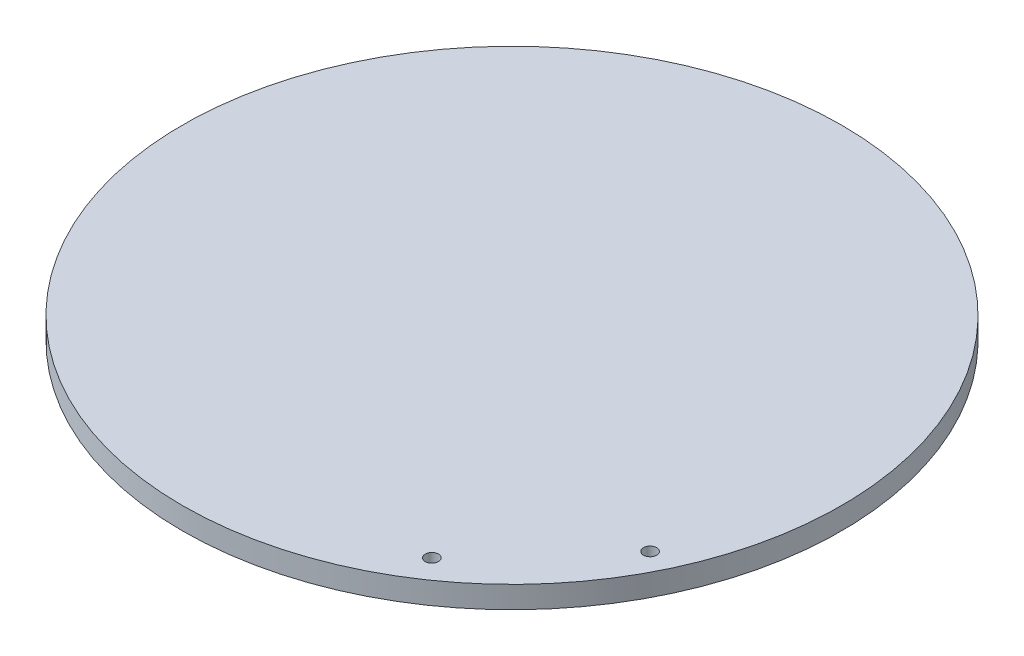
SolidWorks part; units mm, degrees
ref_plane "Front Plane" through (0, 0, 0) normal (0, 0, 1) x (1, 0, 0)
ref_plane "Top Plane" through (0, 0, 0) normal (0, 1, 0) x (1, 0, 0)
ref_plane "Right Plane" through (0, 0, 0) normal (1, 0, 0) x (0, 0, -1)
sketch "Sketch1" plane through (0, 0, 0) normal (0, 1, 0) x (1, 0, 0)
  circle A0 centre (0, 0) radius 150
  dimension "D1" = 300
extrude "Boss-Extrude1" add sketch "Sketch1" along normal blind 10
sketch "Sketch5" plane through (0, 10, 0) normal (0, 1, 0) x (1, 0, 0)
  circle A0 centre (77.3594, -113.8288) radius 3
  circle A1 centre (124.4872, -61.6516) radius 3
  point P4 (-109.0399, -20.2608)
  point P5 (0, 0)
  dimension "D1" = 6
  dimension "D2" = 6
  dimension "D3" = 70.31
extrude "Cut-Extrude1" cut sketch "Sketch5" against normal through all
